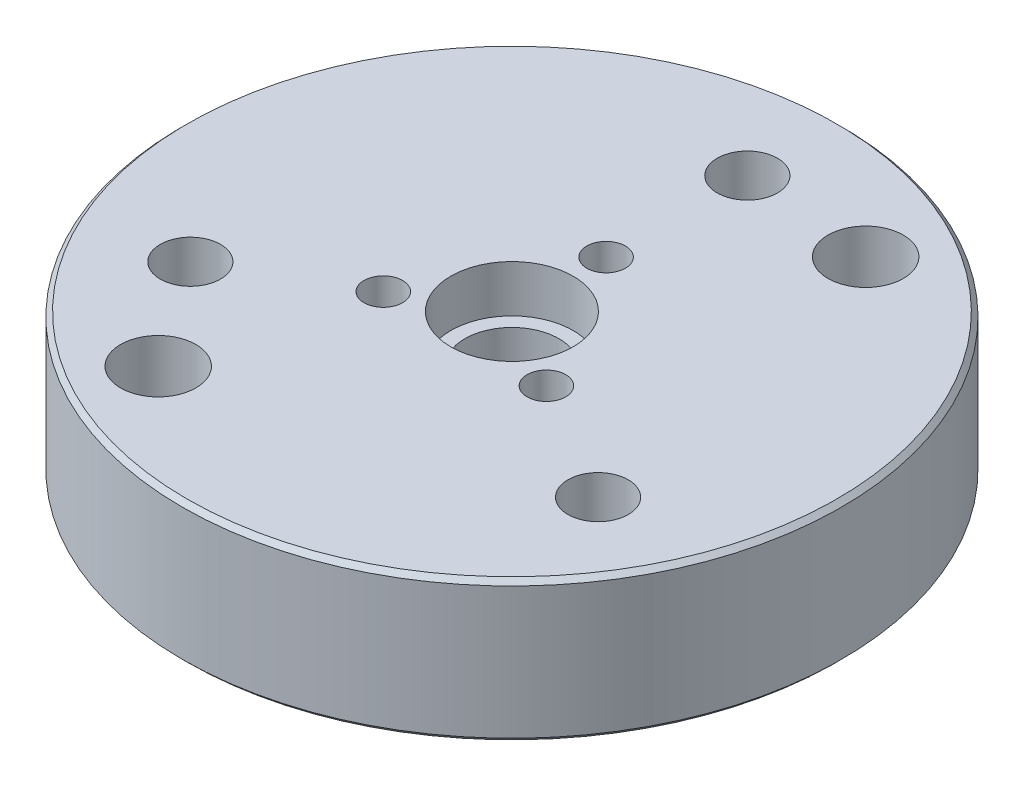
SolidWorks part; units mm, degrees
material "Plain Carbon Steel"
ref_plane "Front Plane" through (0, 0, 0) normal (0, 0, 1) x (1, 0, 0)
ref_plane "Top Plane" through (0, 0, 0) normal (0, 1, 0) x (1, 0, 0)
ref_plane "Right Plane" through (0, 0, 0) normal (1, 0, 0) x (0, 0, -1)
sketch "Sketch1" plane through (0, 0, 0) normal (0, 1, 0) x (1, 0, 0)
  circle A0 centre (0, 0) radius 35
  dimension "D1" = 70
extrude "Boss-Extrude1" add sketch "Sketch1" along normal blind 15
sketch "Sketch2" plane through (0, 15, 0) normal (0, 1, 0) x (1, 0, 0)
  circle A0 centre (0, 0) radius 5
  dimension "D1" = 10
extrude "Cut-Extrude1" cut sketch "Sketch2" against normal up to next
sketch "Sketch3" plane through (0, 15, 0) normal (0, 1, 0) x (1, 0, 0)
  circle A0 centre (0, 0) radius 6.5
  dimension "D1" = 13
extrude "Cut-Extrude2" cut sketch "Sketch3" against normal blind 5
sketch "Sketch4" plane through (0, 15, 0) normal (0, 1, 0) x (1, 0, 0)
  circle A0 centre (0, 10) radius 2.05 construction
  circle A1 centre (8.6603, -5) radius 2.05 construction
  circle A2 centre (-8.6603, -5) radius 2.05 construction
  circle A3 centre (0, 10) radius 2.05
  circle A4 centre (8.6603, -5) radius 2.05
  circle A5 centre (-8.6603, -5) radius 2.05
extrude "Cut-Extrude3" cut sketch "Sketch4" against normal up to next
hole_wizard "M6 Clearance Hole1" positions "Sketch7" profile "Sketch6" hole size "M6" standard "ISO" end condition through all
sketch "Sketch7" plane through (0, 0, 0) normal (0, -1, 0) x (-1, 0, 0)
  point P0 (0, 25)
  point P3 (21.6506, -12.5)
  point P6 (-21.6506, -12.5)
sketch "Sketch6" plane through (0, 0, -25) normal (1, 0, 0) x (0, 0, -1)
  line L0 (0, 0) -> (0, 15)
  line L1 (0, 15) -> (3.2, 15)
  line L2 (3.2, 15) -> (3.2, 0)
  line L5 (3.2, 0) -> (0, 0)
  line L11 (0, -6.35) -> (0, 107.95) construction
  dimension "Thru Hole Dia." = 6.4
  dimension "Thru Hole Depth" = 15
hole_wizard "Ø8.0mm Dowel Hole1" positions "Sketch10" profile "Sketch9" hole size "Ø8.0" standard "ISO" end condition through all
sketch "Sketch10" plane through (0, 0, 0) normal (0, -1, 0) x (-1, 0, 0)
  point P0 (-13.75, 23.8157)
  point P3 (13.75, -23.8157)
sketch "Sketch9" plane through (13.75, 0, -23.8157) normal (1, 0, 0) x (0, 0, -1)
  line L0 (0, 0) -> (0, 15)
  line L1 (0, 15) -> (4, 15)
  line L2 (4, 15) -> (4, 0)
  line L5 (4, 0) -> (0, 0)
  line L11 (0, -6.35) -> (0, 107.95) construction
  dimension "Thru Hole Dia." = 8
  dimension "Thru Hole Depth" = 15
chamfer "Chamfer1" distance 0.5 angle 45 2 edges at (0, 0, 35) (0, 15, 35)
